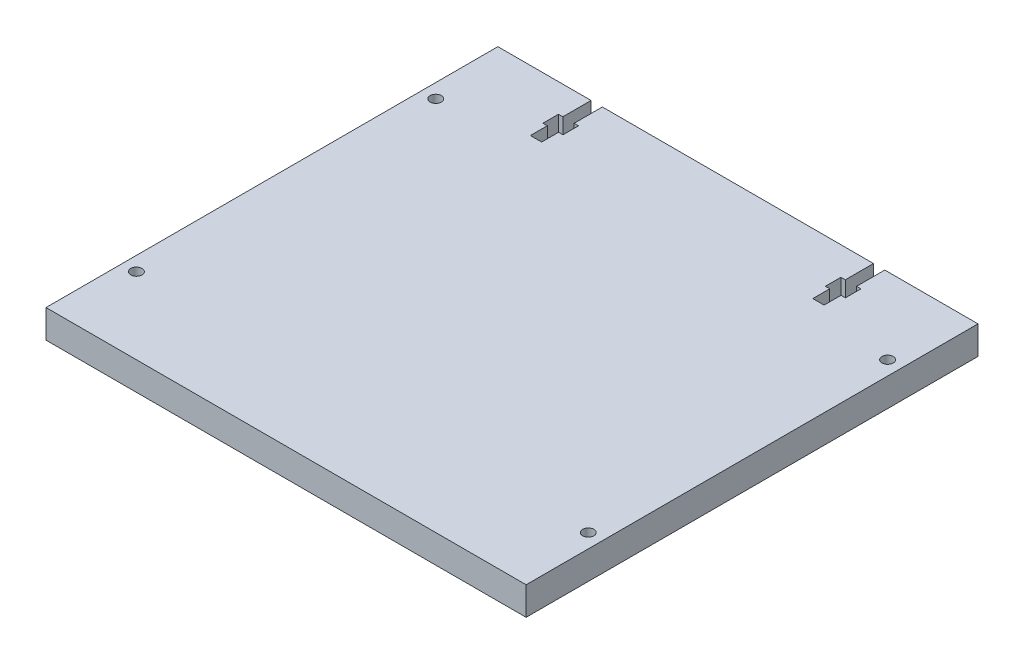
SolidWorks part; units mm, degrees
ref_plane "Front Plane" through (0, 0, 0) normal (0, 0, 1) x (1, 0, 0)
ref_plane "Top Plane" through (0, 0, 0) normal (0, 1, 0) x (1, 0, 0)
ref_plane "Right Plane" through (0, 0, 0) normal (1, 0, 0) x (0, 0, -1)
sketch "Sketch1" plane through (0, 0, 0) normal (0, 0, 1) x (1, 0, 0)
  line L1 (0, 0) -> (170, 0)
  line L2 (0, 0) -> (0, 10)
  line L3 (0, 10) -> (170, 10)
  line L4 (170, 0) -> (170, 10)
  dimension "D1" = 10
  dimension "D2" = 170
extrude "Boss-Extrude1" add sketch "Sketch1" along normal blind 160
sketch "Esquisse1" plane through (0, 0, 0) normal (0, -1, 0) x (1, 0, 0)
  line L0 (0, 160) -> (170, 160) construction
  line L1 (0, 160) -> (0, 0) construction
  line L2 (0, 80) -> (21.4077, 80) construction
  line L3 (85, 0) -> (85, 25.6676) construction
  line L4 (0, 0) -> (170, 0) construction
  line L5 (170, 80) -> (148.5923, 80) construction
  circle A0 centre (5, 133) radius 2
  circle A1 centre (5, 27) radius 2
  circle A2 centre (5, 133) radius 2
  circle A3 centre (5, 27) radius 2
  circle A4 centre (165, 27) radius 2
  circle A5 centre (165, 133) radius 2
  circle A6 centre (165, 27) radius 2
  circle A7 centre (165, 133) radius 2
  dimension "D1" = 4
  dimension "D2" = 27
  dimension "D3" = 5
extrude "Enlèv. mat.-Extru.2" cut sketch "Esquisse1" against normal blind 10 contours A0 | A1 | A4 | A5
sketch "Esquisse2" plane through (0, 0, 0) normal (0, -1, 0) x (-1, 0, 0)
  line L0 (-33, 0) -> (-33, -10)
  line L1 (0, 0) -> (-170, 0) construction
  line L2 (-33, -10) -> (-31.45, -10)
  line L3 (-31.45, -10) -> (-31.45, -15.5)
  line L4 (-31.45, -15.5) -> (-33, -15.5)
  line L5 (-33, -15.5) -> (-33, -21.5)
  line L6 (-33, -21.5) -> (-37, -21.5)
  line L7 (-33, 0) -> (-37, 0)
  line L8 (-35, -21.5) -> (-35, 0) construction
  line L9 (0, -160) -> (0, 0) construction
  line L10 (-37, -15.5) -> (-37, -21.5)
  line L11 (-38.55, -15.5) -> (-37, -15.5)
  line L12 (-38.55, -10) -> (-38.55, -15.5)
  line L13 (-37, -10) -> (-38.55, -10)
  line L14 (-37, 0) -> (-37, -10)
  line L15 (-85, 0) -> (-85, -58.4679) construction
  line L16 (-33, 0) -> (-33, -10)
  line L17 (-33, -10) -> (-31.45, -10)
  line L18 (-31.45, -10) -> (-31.45, -15.5)
  line L19 (-31.45, -15.5) -> (-33, -15.5)
  line L20 (-33, -15.5) -> (-33, -21.5)
  line L21 (-37, -15.5) -> (-37, -21.5)
  line L22 (-38.55, -15.5) -> (-37, -15.5)
  line L23 (-38.55, -10) -> (-38.55, -15.5)
  line L24 (-37, -10) -> (-38.55, -10)
  line L25 (-37, 0) -> (-37, -10)
  line L26 (-135, -21.5) -> (-135, 0) construction
  line L27 (-133, 0) -> (-133, -10)
  line L28 (-133, -10) -> (-131.45, -10)
  line L29 (-131.45, -10) -> (-131.45, -15.5)
  line L30 (-131.45, -15.5) -> (-133, -15.5)
  line L31 (-133, -15.5) -> (-133, -21.5)
  line L32 (-137, -15.5) -> (-137, -21.5)
  line L33 (-138.55, -15.5) -> (-137, -15.5)
  line L34 (-138.55, -10) -> (-138.55, -15.5)
  line L35 (-137, -10) -> (-138.55, -10)
  line L36 (-137, 0) -> (-137, -10)
  line L37 (-133, 0) -> (-133, -10)
  line L38 (-133, -10) -> (-131.45, -10)
  line L39 (-131.45, -10) -> (-131.45, -15.5)
  line L40 (-131.45, -15.5) -> (-133, -15.5)
  line L41 (-133, -15.5) -> (-133, -21.5)
  line L42 (-137, 0) -> (-133, 0)
  line L43 (-137, -21.5) -> (-133, -21.5)
  line L44 (-137, -15.5) -> (-137, -21.5)
  line L45 (-138.55, -15.5) -> (-137, -15.5)
  line L46 (-138.55, -10) -> (-138.55, -15.5)
  line L47 (-137, -10) -> (-138.55, -10)
  line L48 (-137, 0) -> (-137, -10)
  line M10 (0, 0) -> (-170, 0)
  dimension "D1" = 2
  dimension "D2" = 2
  dimension "D3" = 10
  dimension "D4" = 5.5
  dimension "D5" = 6
  dimension "D6" = 35
  dimension "D7" = 7.1
extrude "Enlèv. mat.-Extru.3" cut sketch "Esquisse2" against normal blind 10 contours L32 L43 L31 L30 L29 L28 L27 L36 L35 L34 L33 M10 | L14 L13 L12 L11 L10 L6 L5 L4 L3 L2 L0 M10
